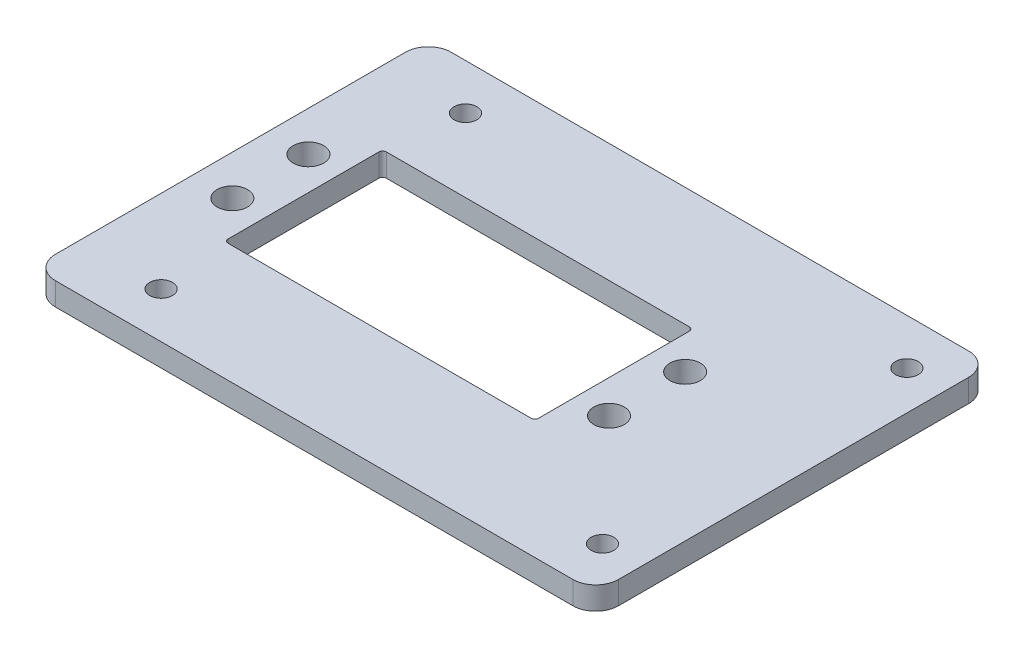
SolidWorks part; units mm, degrees
material "Thornel Mat VMA"
ref_plane "前视基准面" through (0, 0, 0) normal (0, 0, 1) x (1, 0, 0)
ref_plane "上视基准面" through (0, 0, 0) normal (0, 1, 0) x (1, 0, 0)
ref_plane "右视基准面" through (0, 0, 0) normal (1, 0, 0) x (0, 0, -1)
other "Configuration Table"
sketch "草图1" plane through (0, 0, 0) normal (0, 1, 0) x (1, 0, 0)
  line L0 (0, 0) -> (0, 29.6725) construction
  line L1 (-30, -26) -> (30, -26)
  line L2 (-30, -26) -> (-30, 26)
  line L3 (-30, 26) -> (30, 26)
  line L4 (30, -26) -> (30, 26)
  line L5 (-30, -26) -> (30, 26) construction
  line L6 (-30, 26) -> (30, -26) construction
  line L11 (-17.0509, -14.7775) -> (16.6579, 14.4368) construction
  line L12 (9.89, 0) -> (9.89, 37.58) construction
  line L13 (-20.4, -10.4) -> (20.4, -10.4)
  line L14 (-20.4, -10.4) -> (-20.4, 10.4)
  line L15 (-20.4, 10.4) -> (20.4, 10.4)
  line L16 (20.4, -10.4) -> (20.4, 10.4)
  line L17 (-20.4, -10.4) -> (20.4, 10.4) construction
  line L18 (-20.4, 10.4) -> (20.4, -10.4) construction
  line L19 (0, 0) -> (43.0948, 0) construction
  line L20 (30, 26) -> (44, 26)
  line L21 (44, 26) -> (44, -26)
  line L22 (30, -26) -> (44, -26)
  circle A0 centre (24.75, 5) radius 2
  circle A1 centre (24.75, -5) radius 2
  circle A2 centre (-24.75, -5) radius 2
  circle A3 centre (-24.75, 5) radius 2
  circle A8 centre (-19.11, 20) radius 1.5
  circle A9 centre (-19.11, -20) radius 1.5
  circle A10 centre (38.89, -20) radius 1.5
  circle A11 centre (38.89, 20) radius 1.5
  point P0 (0, 0)
  point P6 (0, 0)
  point P13 (0, 0)
  point P38 (44, 0)
  dimension "D5" = 4
  dimension "D8" = 9.89
  dimension "D7" = 49.5
  dimension "D9" = 3
  dimension "D10" = 20
  dimension "D1" = 60
  dimension "D2" = 52
  dimension "D3" = 40.8
  dimension "D4" = 20.8
  dimension "D6" = 5
  dimension "D11" = 29
  dimension "D12" = 14
extrude "凸台-拉伸1" add sketch "草图1" along normal blind 3 contours L1 L4 L3 L2 A3 A2 L16 L13 L14 L15 A0 A1 A8 A9 | L4 L22 L21 L20 A10 A11
fillet "圆角1" radius 0.5 4 edges at (20.4, 1.5, 10.4) (-20.4, 1.5, 10.4) (20.4, 1.5, -10.4) (-20.4, 1.5, -10.4)
fillet "圆角2" radius 3 4 edges at (44, 1.5, -26) (44, 1.5, 26) (-30, 1.5, 26) (-30, 1.5, -26)
